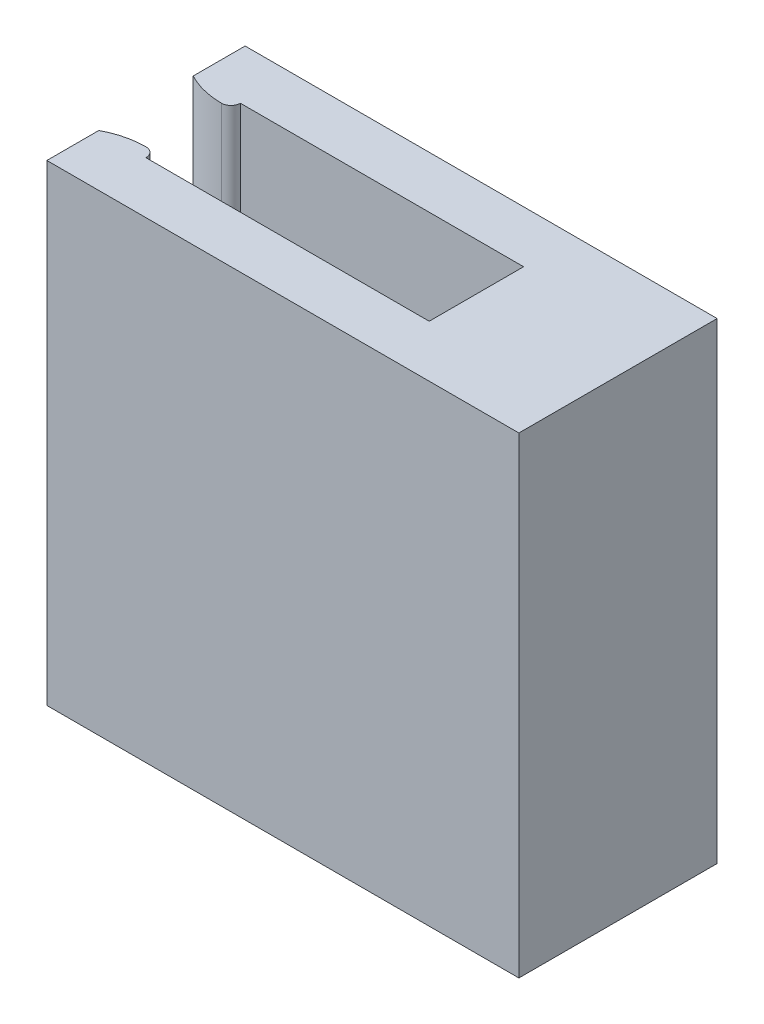
SolidWorks part; units mm, degrees
ref_plane "Front Plane" through (0, 0, 0) normal (0, 0, 1) x (1, 0, 0)
ref_plane "Top Plane" through (0, 0, 0) normal (0, 1, 0) x (1, 0, 0)
ref_plane "Right Plane" through (0, 0, 0) normal (1, 0, 0) x (0, 0, -1)
sketch "Sketch1" plane through (0, 0, 0) normal (0, 1, 0) x (1, 0, 0)
  line L1 (-15, 37.5) -> (15, 37.5)
  line L2 (-15, 37.5) -> (-15, -37.5)
  line L3 (-15, -37.5) -> (15, -37.5)
  line L4 (15, 37.5) -> (15, -37.5)
  line L5 (-15, 37.5) -> (15, -37.5) construction
  line L6 (-15, -37.5) -> (15, 37.5) construction
  point P0 (0, 0)
  dimension "D1" = 30
  dimension "D2" = 75
extrude "Main Block" add sketch "Sketch1" along normal mid plane 50
sketch "Sketch2" plane through (0, 0, 37.5) normal (0, 0, 1) x (1, 0, 0)
  line L0 (0, -41.25) -> (0, 41.25) construction
  line L1 (-15, -25) -> (15, -25) construction
  circle A0 centre (0, -15) radius 5
  dimension "D1" = 10
  dimension "D2" = 10
extrude "Frame Hole" cut sketch "Sketch2" against normal up to next
sketch "EM Rod Holes Sketch" plane through (15, 0, 0) normal (1, 0, 0) x (0, 0, -1)
  line L0 (-37.5, 25) -> (37.5, 25) construction
  line L1 (0, 11) -> (0, -11) construction
  circle A0 centre (-15, 15) radius 5
  circle A1 centre (15, 15) radius 5
  dimension "D1" = 10
  dimension "D4" = 10
  dimension "D2" = 10
  dimension "D3" = 15
  dimension "D5" = 10
  dimension "D6" = 15
extrude "EM Rod Holes" cut sketch "EM Rod Holes Sketch" against normal up to next
sketch "Sketch4" plane through (0, -25, 0) normal (0, -1, 0) x (1, 0, 0)
  line L0 (-15, 37.5) -> (-25, 37.5)
  line L1 (-25, 37.5) -> (-25, 36.4)
  line L2 (-25, 36.4) -> (-18, 36.4)
  line L3 (-18, 36.4) -> (-18, 34.4)
  line L4 (-18, 34.4) -> (-25, 34.4)
  line L5 (-25, 34.4) -> (-25, 33.3)
  line L6 (-25, 33.3) -> (-15, 33.3)
  line L7 (-15, 33.3) -> (-15, 37.5)
  line L8 (-15, 37.5) -> (15, 37.5) construction
  line L9 (-15, -37.5) -> (-15, 37.5) construction
  line L10 (-25, 36.4) -> (-15, 36.4) construction
  line L11 (-25, 33.3) -> (-15, 33.3) construction
  line L12 (-25, 34.4) -> (-15, 34.4) construction
  line L13 (-25, 36.2) -> (-15, 36.2) construction
  line L14 (-25, 34.6) -> (-15, 34.6) construction
  line L15 (-24.2, 37.5) -> (-24.2, 33.3) construction
  arc A0 (-25, 36.4) -> (-24.2, 36.2) centre (-24.2, 37.9) ccw
  arc A1 (-25, 34.4) -> (-24.2, 34.6) centre (-24.2, 32.9) cw
  arc A2 (-24.2, 36.2) -> (-24, 36.4) centre (-24.2, 36.4) ccw
  arc A3 (-24.2, 34.6) -> (-24, 34.4) centre (-24.2, 34.4) cw
  line M16 (-15, 37.5) -> (-15, -37.5)
  dimension "D9" = 0.2
  dimension "D1" = 10
  dimension "D2" = 7
  dimension "D3" = 2
  dimension "D4" = 1.1
  dimension "D5" = 0.2
  dimension "D6" = 0.2
  dimension "D7" = 6.2
  dimension "D8" = 0.2
extrude "Boss-Extrude1" add sketch "Sketch4" against normal blind 10 contours L5 L6 L0 L1 L2 L3 L4 M16 | A0 A2 L2 | A3 A1 L4
sketch "Sketch5" plane through (0, 0, 0) normal (0, 1, 0) x (1, 0, 0)
  line L1 (-15, 37.5) -> (15, 37.5)
  line L2 (-15, 37.5) -> (-15, -37.5)
  line L3 (-15, -37.5) -> (15, -37.5)
  line L4 (15, 37.5) -> (15, -37.5)
extrude "Cut-Extrude1" cut sketch "Sketch5" against normal through all both and the other way through all
